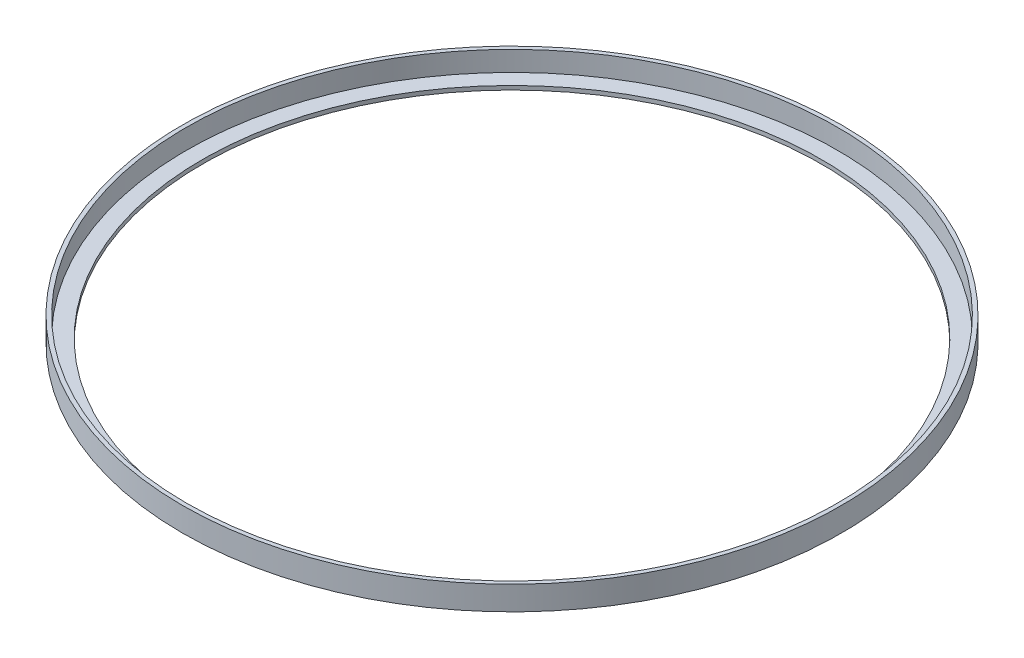
SolidWorks part; units mm, degrees
ref_plane "Front Plane" through (0, 0, 0) normal (0, 0, 1) x (1, 0, 0)
ref_plane "Top Plane" through (0, 0, 0) normal (0, 1, 0) x (1, 0, 0)
ref_plane "Right Plane" through (0, 0, 0) normal (1, 0, 0) x (0, 0, -1)
sketch "Sketch1" plane through (0, 0, 0) normal (0, 1, 0) x (1, 0, 0)
  circle A0 centre (0, 0) radius 31
  circle A1 centre (0, 0) radius 33
  dimension "D1" = 2
  dimension "D2" = 66
extrude "Boss-Extrude1" add sketch "Sketch1" along normal blind 0.4
sketch "Sketch2" plane through (0, 0.4, 0) normal (0, 1, 0) x (1, 0, 0)
  circle A0 centre (0, 0) radius 33 construction
  circle A1 centre (0, 0) radius 33
  circle A2 centre (0, 0) radius 32.6
  dimension "D1" = 0.4
extrude "Boss-Extrude2" add sketch "Sketch2" along normal blind 2
